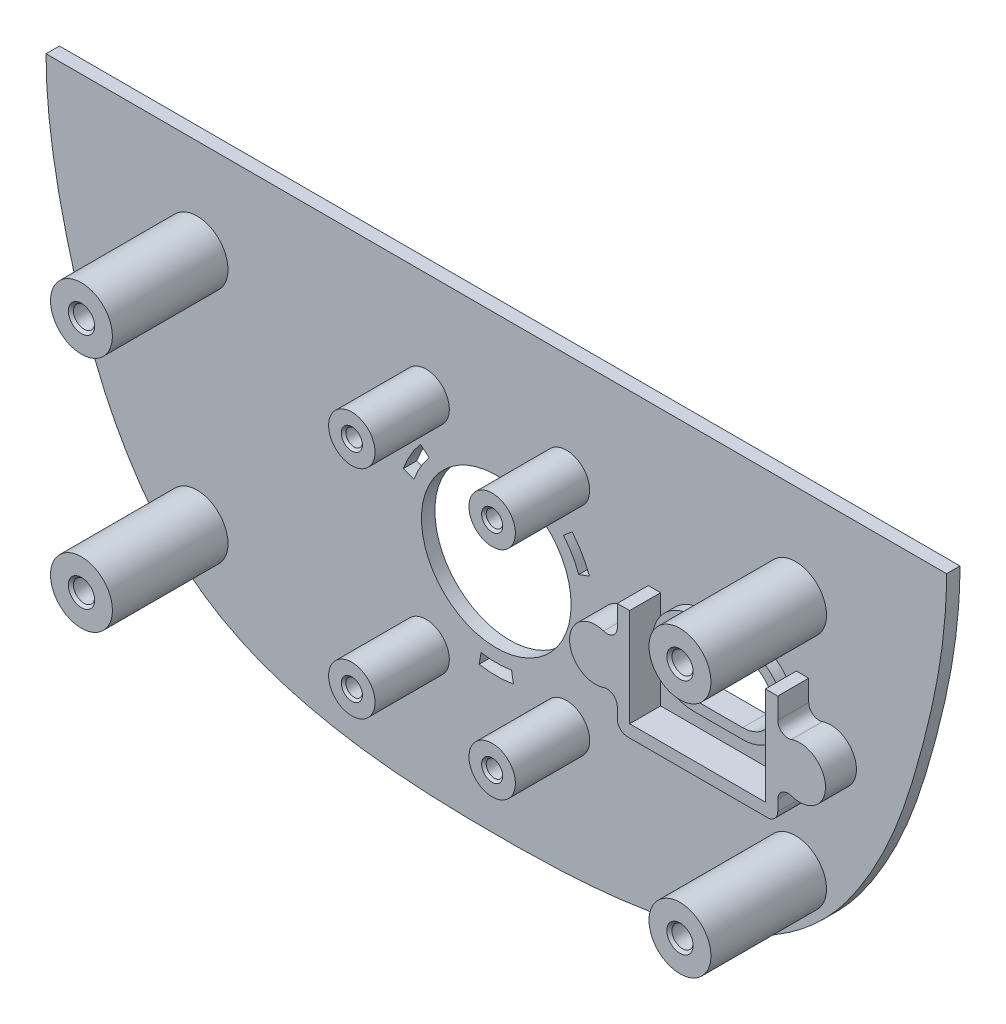
SolidWorks part; units mm, degrees
ref_plane "前视基准面" through (0, 0, 0) normal (0, 0, 1) x (1, 0, 0)
ref_plane "上视基准面" through (0, 0, 0) normal (0, 1, 0) x (1, 0, 0)
ref_plane "右视基准面" through (0, 0, 0) normal (1, 0, 0) x (0, 0, -1)
sketch "草图1" plane through (0, 0, 0) normal (0, 0, 1) x (1, 0, 0)
  line L0 (-43.6339, 20.8) -> (43.6339, 20.8)
  line L1 (0, 0) -> (0, 20.8) construction
  line L2 (0, 2.6389) -> (0, -26.4976) construction
  line L3 (-43.8839, 20.8) -> (-43.6339, 20.8) construction
  line L4 (43.6339, 20.8) -> (43.8839, 20.8) construction
  spline S0 degree 1 poles (43.6339, 20.8) (-43.6339, 20.8) knots 0 0 1 1 construction
  spline S2 degree 3 poles (43.8839, 20.8) (43.8839, 19.295) (43.8062, 17.7915) (43.52, 14.7988) (43.3123, 13.3161) (42.5375, 8.9007) (41.8192, 6.0001) (40.5836, 1.6829) (40.1439, 0.2457) (39.3985, -1.8678) (39.1359, -2.5656) (38.573, -3.9436) (38.2722, -4.6234) (37.6336, -5.9657) (37.2957, -6.6281) (36.5877, -7.9377) (36.2184, -8.5853) (35.4385, -9.8611) (35.0263, -10.4915) (34.1584, -11.7163) (33.7041, -12.3092) (32.2665, -14.0164) (31.2055, -15.0562) (29.4611, -16.4697) (28.852, -16.9188) (27.6068, -17.7539) (26.9691, -18.1417) (25.0123, -19.2187) (23.6479, -19.8186) (21.529, -20.5757) (20.8111, -20.8046) (19.3694, -21.2188) (18.6436, -21.4048) (16.4547, -21.9124) (14.9785, -22.1827) (12.0052, -22.6123) (10.5133, -22.771) (7.5219, -23.0045) (6.0215, -23.0792) (3.0202, -23.1704) (1.5191, -23.1868) (-2.9848, -23.1872) (-5.9875, -23.1229) (-10.4778, -22.7745) (-11.9721, -22.6162) (-14.9316, -22.1906) (-16.3992, -21.9233) (-19.3046, -21.2537) (-20.7426, -20.8527) (-22.8661, -20.1) (-23.5714, -19.8225) (-24.9481, -19.214) (-25.6201, -18.8828) (-27.5852, -17.806) (-28.8284, -16.9783) (-30.586, -15.5606) (-31.1547, -15.057) (-32.2278, -14.0074) (-32.7355, -13.4591) (-34.1777, -11.7484) (-35.0338, -10.5222) (-36.212, -8.5968) (-36.5857, -7.9421) (-37.3004, -6.6198) (-37.6415, -5.9507) (-38.2859, -4.5941) (-38.5893, -3.9066) (-39.1568, -2.5126) (-39.4214, -1.806) (-40.1675, 0.3181) (-40.6028, 1.7467) (-41.8315, 6.0482) (-42.5451, 8.9372) (-43.571, 14.7965) (-43.8839, 17.7666) (-43.8839, 20.8) knots 0 0 0 0 0.03125 0.03125 0.0625 0.0625 0.125 0.125 0.15625 0.15625 0.171875 0.171875 0.1875 0.1875 0.203125 0.203125 0.21875 0.21875 0.234375 0.234375 0.25 0.25 0.28125 0.28125 0.296875 0.296875 0.3125 0.3125 0.34375 0.34375 0.359375 0.359375 0.375 0.375 0.40625 0.40625 0.4375 0.4375 0.46875 0.46875 0.5 0.5 0.5625 0.5625 0.59375 0.59375 0.625 0.625 0.65625 0.65625 0.671875 0.671875 0.6875 0.6875 0.71875 0.71875 0.734375 0.734375 0.75 0.75 0.78125 0.78125 0.796875 0.796875 0.8125 0.8125 0.828125 0.828125 0.84375 0.84375 0.875 0.875 0.9375 0.9375 1 1 1 1 construction
  spline S3 degree 3 poles (43.6339, 20.8) (43.6339, 17.8164) (43.166, 13.3283) (41.9353, 7.5099) (40.781, 3.1865) (39.4714, -1.1117) (37.8005, -5.2204) (35.6894, -9.1296) (33.1326, -12.818) (29.9822, -15.9015) (26.2498, -18.4017) (22.1965, -20.1817) (16.4294, -21.8047) (9.015, -22.8062) (0.0168, -23.0018) (-7.4766, -22.8407) (-13.4305, -22.2105) (-17.8104, -21.4105) (-22.1023, -20.2168) (-26.2289, -18.4139) (-29.2983, -16.3652) (-31.5469, -14.3756) (-33.5521, -12.2089) (-35.6737, -9.1574) (-37.8137, -5.1999) (-39.4986, -1.0337) (-41.2304, 4.67) (-42.6569, 10.4354) (-43.4782, 16.3005) (-43.6339, 19.3043) (-43.6339, 20.8) knots 0 0 0 0 0.0625 0.09375 0.125 0.15625 0.1875 0.21875 0.25 0.28125 0.3125 0.34375 0.375 0.4375 0.5 0.5625 0.59375 0.625 0.65625 0.6875 0.71875 0.734375 0.75 0.78125 0.8125 0.84375 0.875 0.9375 0.96875 1 1 1 1
  dimension "D1" = 20.8
  dimension "D2" = 43.8839
  dimension "D3" = 0.25
extrude "凸台-拉伸1" add sketch "草图1" against normal blind 1.3
sketch "草图2" plane through (0, 0, 0) normal (0, 0, 1) x (1, 0, 0)
  line L0 (20.125, 2) -> (24.875, 2) construction
  line L1 (20.125, 5) -> (24.875, 5)
  line L2 (20.125, -1) -> (24.875, -1)
  circle A0 centre (0, 0) radius 7.25
  arc A1 (20.125, 5) -> (20.125, -1) centre (20.125, 2) ccw
  arc A2 (24.875, -1) -> (24.875, 5) centre (24.875, 2) ccw
  point P2 (22.5, 2)
  dimension "D1" = 14.5
  dimension "D3" = 6
  dimension "D4" = 4.75
  dimension "D2" = 2
  dimension "D5" = 22.5
extrude "切除-拉伸1" cut sketch "草图2" against normal through all
sketch "草图3" plane through (0, 0, 0) normal (0, 0, 1) x (1, 0, 0)
  circle A0 centre (-29, 11.5) radius 3
  circle A1 centre (-6.8, 10.5) radius 2.25
  point P5 (0, 0)
  dimension "D1" = 6
  dimension "D2" = 4.5
  dimension "D3" = 22.2
  dimension "D4" = 1
  dimension "D5" = 10.5
  dimension "D6" = 6.8
extrude "凸台-拉伸2" add sketch "草图3" along normal blind 7.2
sketch "草图4" plane through (0, 0, 7.2) normal (0, 0, 1) x (1, 0, 0)
  circle A1 centre (-29, 11.5) radius 3
  circle A2 centre (-29, 11.5) radius 3
  dimension "D1" = 0
extrude "凸台-拉伸3" add sketch "草图4" along normal blind 4
hole_wizard "M2 螺纹孔1" positions "草图5" profile "草图6" tap size "M2" standard "GB"
sketch "草图5" plane through (0, 0, 7.2) normal (0, 0, 1) x (1, 0, 0)
  point P0 (-6.8, 10.5)
sketch "草图6" plane through (-6.8, 10.5, 7.2) normal (1, 0, 0) x (0, -1, 0)
  line L0 (0, 0) -> (0, 5.6807)
  line L1 (0, 5.6807) -> (0.8, 5.2)
  line L2 (0.8, 5.2) -> (0.8, 0.225)
  line L3 (0.8, 0.225) -> (1.025, 0)
  line L5 (1.025, 0) -> (0, 0)
  line L6 (-0.8, 0.225) -> (-1.025, 0) construction
  line L10 (0, 5.6807) -> (-0.8, 5.2) construction
  line L11 (0, -6.35) -> (0, 107.95) construction
  dimension "螺纹孔钻头直径" = 1.6
  dimension "螺纹孔钻头深度" = 5.2
  dimension "近端锥形沉头孔直径" = 2.05
  dimension "近端锥形沉头孔角度" = 90
  dimension "导头角度" = 118
cosmetic thread "孔螺蚊线2" parameters "D1"=4, "D2"=2
hole_wizard "M2.5 螺纹孔1" positions "草图7" profile "草图8" tap size "M2.5" standard "GB"
sketch "草图7" plane through (0, 0, 11.2) normal (0, 0, 1) x (1, 0, 0)
  point P0 (-29, 11.5)
sketch "草图8" plane through (-29, 11.5, 11.2) normal (1, 0, 0) x (0, -1, 0)
  line L0 (0, 0) -> (0, 6.9659)
  line L1 (0, 6.9659) -> (1.025, 6.35)
  line L2 (1.025, 6.35) -> (1.025, 0.25)
  line L3 (1.025, 0.25) -> (1.275, 0)
  line L5 (1.275, 0) -> (0, 0)
  line L6 (-1.025, 0.25) -> (-1.275, 0) construction
  line L10 (0, 6.9659) -> (-1.025, 6.35) construction
  line L11 (0, -6.35) -> (0, 107.95) construction
  dimension "螺纹孔钻头直径" = 2.05
  dimension "螺纹孔钻头深度" = 6.35
  dimension "近端锥形沉头孔直径" = 2.55
  dimension "近端锥形沉头孔角度" = 90
  dimension "导头角度" = 118
cosmetic thread "孔螺蚊线3" parameters "D1"=5, "D2"=2.5
mirror "镜向1" about plane through (0, 0, 0) normal (0, 1, 0) of "M2.5 螺纹孔1", "M2 螺纹孔1", "凸台-拉伸3", "凸台-拉伸2"
cosmetic thread "孔螺蚊线4" parameters "D1"=4, "D2"=2
cosmetic thread "孔螺蚊线5" parameters "D1"=5, "D2"=2.5
mirror "镜向2" about plane through (0, 0, 0) normal (1, 0, 0) of "凸台-拉伸2", "凸台-拉伸3", "M2 螺纹孔1", "M2.5 螺纹孔1", "镜向1"
cosmetic thread "孔螺蚊线6" parameters "D1"=5, "D2"=2.5
cosmetic thread "孔螺蚊线7" parameters "D1"=4, "D2"=2
cosmetic thread "孔螺蚊线8" parameters "D1"=5, "D2"=2.5
cosmetic thread "孔螺蚊线9" parameters "D1"=4, "D2"=2
sketch "草图9" plane through (0, 0, 0) normal (0, 0, 1) x (1, 0, 0)
  line L0 (15.925, 5.35) -> (15.925, -4.15)
  line L1 (14.725, 5.35) -> (30.275, 5.35)
  line L2 (14.725, 5.35) -> (14.725, -5.35)
  line L3 (14.725, -5.35) -> (30.275, -5.35)
  line L4 (30.275, 5.35) -> (30.275, -5.35)
  line L5 (15.925, -4.15) -> (29.075, -4.15)
  line L6 (29.075, 5.35) -> (29.075, -4.15)
  circle A0 centre (12.6, 0) radius 2.5
  circle A1 centre (32.4, 0) radius 2.5
  point P8 (0, 0)
  dimension "D2" = 5
  dimension "D3" = 19.8
  dimension "D1" = 12.6
  dimension "D4" = 2.125
  dimension "D5" = 2.125
  dimension "D6" = 5.35
  dimension "D7" = 10.7
  dimension "D8" = 1.2
extrude "凸台-拉伸4" add sketch "草图9" along normal blind 3 contours L2 A0 | A1 L4 L1 L6 L5 L0 L2 A0 L3 | L2 A0 | L4 A1 | L4 A1
fillet "圆角1" radius 1 2 edges at (30.275, -5.35, 1.5) (14.725, -5.35, 1.5)
fillet "圆角2" radius 1 4 edges at (14.725, -1.317, 1.5) (14.725, 1.317, 1.5) (30.275, 1.317, 1.5) (30.275, -1.317, 1.5)
sketch "草图10" plane through (0, 0, 0) normal (0, 0, 1) x (1, 0, 0)
  line L4 (20.125, -2) -> (24.875, -2)
  line L5 (24.875, 6) -> (20.125, 6)
  line L6 (20.125, -2) -> (24.875, -2)
  line L7 (24.875, 6) -> (20.125, 6)
  arc A4 (20.125, 6) -> (20.125, -2) centre (20.125, 2) ccw
  arc A5 (24.875, -2) -> (24.875, 6) centre (24.875, 2) ccw
  arc A6 (20.125, 6) -> (20.125, -2) centre (20.125, 2) ccw
  arc A7 (24.875, -2) -> (24.875, 6) centre (24.875, 2) ccw
  line M8 (24.875, -1) -> (20.125, -1)
  arc M9 (20.125, -1) -> (20.125, 5) centre (20.125, 2) cw
  line M10 (20.125, 5) -> (24.875, 5)
  arc M11 (24.875, 5) -> (24.875, -1) centre (24.875, 2) cw
  dimension "D1" = 1
extrude "凸台-拉伸5" add sketch "草图10" along normal blind 1 contours L6 A7 L7 A6 M11 M8 M9 M10
sketch "草图11" plane through (0, 0, 0) normal (0, 0, 1) x (1, 0, 0)
  line L0 (0, 0) -> (-1.667, -9.4542)
  line L1 (0, 0) -> (1.667, -9.4542)
  line L2 (0, 0) -> (0, -6.6245) construction
  line L3 (0, 0) -> (-7.354, 6.1708)
  line L4 (0, 0) -> (-9.021, 3.2834)
  line L5 (0, 0) -> (9.021, 3.2834)
  line L6 (0, 0) -> (7.354, 6.1708)
  circle A0 centre (0, 0) radius 9.6
  circle A1 centre (0, 0) radius 8.5
  point P0 (0, 0)
  point P14 (0, 0)
  dimension "D1" = 1.1
  dimension "D2" = 17
  dimension "D3" = 20
  dimension "D4" = 3
extrude "切除-拉伸2" cut sketch "草图11" against normal through all contours A1 L3 A0 L4 | A1 L5 A0 L6 | A1 L0 A0 L1
